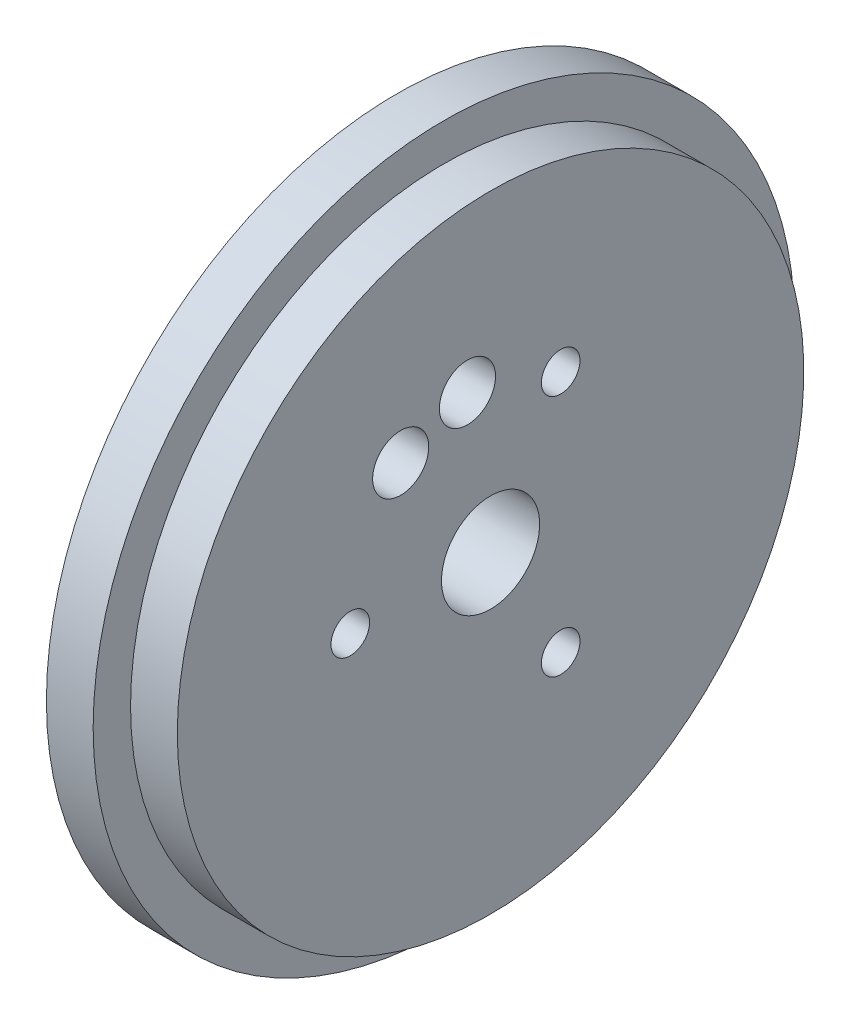
SolidWorks part; units mm, degrees
material "Alumina"
ref_plane "Front Plane" through (0, 0, 0) normal (0, 0, 1) x (1, 0, 0)
ref_plane "Top Plane" through (0, 0, 0) normal (0, 1, 0) x (1, 0, 0)
ref_plane "Right Plane" through (0, 0, 0) normal (1, 0, 0) x (0, 0, -1)
sketch "Axial profile (mm)" plane through (0, 0, 0) normal (0, 0, 1) x (1, 0, 0)
  line L0 (-110, 0) -> (75, 0) construction
  line L1 (135.7, 4.2) -> (143.7, 4.2)
  line L2 (143.7, 4.2) -> (143.7, 26.8)
  line L3 (143.7, 26.8) -> (139.7, 26.8)
  line L4 (139.7, 26.8) -> (139.7, 30)
  line L5 (139.7, 30) -> (135.7, 30)
  line L6 (135.7, 30) -> (135.7, 4.2)
revolve "Full revolution" add sketch "Axial profile (mm)" angle 360 about L0
sketch "Sketch2" plane through (0, 0, 0) normal (1, 0, 0) x (0, 0, -1)
  circle A0 centre (-1.9774, 12.8487) radius 2.4
  circle A1 centre (-7.6872, 10.4836) radius 2.4
  circle A2 centre (-12, 0) radius 1.65
  circle A3 centre (6, -10.3923) radius 1.65
  circle A4 centre (6, 10.3923) radius 1.65
extrude "Axial holes" cut sketch "Sketch2" along normal through all and the other way through all
